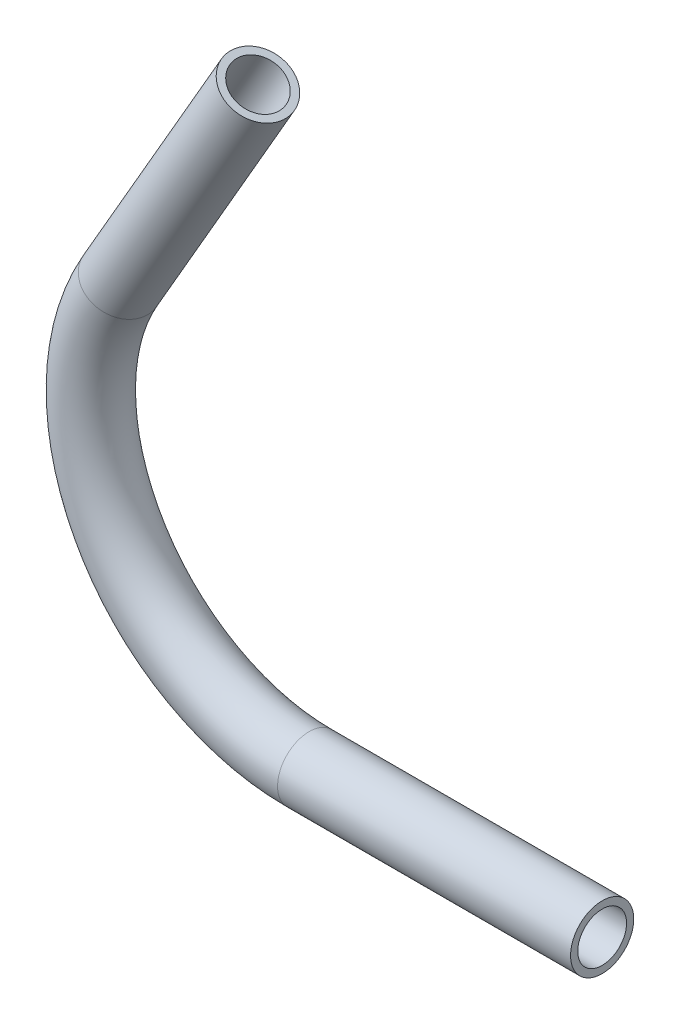
SolidWorks part; units mm, degrees
ref_plane "Plan1" through (0, 0, 0) normal (0, 0, 1) x (1, 0, 0)
ref_plane "Plan2" through (0, 0, 0) normal (0, 1, 0) x (1, 0, 0)
ref_plane "Plan3" through (0, 0, 0) normal (1, 0, 0) x (0, 0, -1)
sketch "Esquisse1" plane through (0, 0, 0) normal (0, 0, 1) x (1, 0, 0)
  line L0 (0, 0) -> (-90.448, 52.2202) construction
  line L1 (0, 0) -> (0, -92.4) construction
  arc A0 (-65.8179, 38) -> (0, -76) centre (0, 0) ccw
  dimension "D1" = 76
sketch "Esquisse2" plane through (0, 0, 0) normal (1, 0, 0) x (0, 0, -1)
  circle A0 centre (0, -76) radius 11
  circle A1 centre (0, -76) radius 8.5
  dimension "D1" = 22
  dimension "D3" = 17
  dimension "D2" = 76
sweep "Base-Balayage" add profiles "Esquisse2" path "Esquisse1"
sketch "Esquisse3" plane through (0, 0, 0) normal (1, 0, 0) x (0, 0, -1)
  circle A0 centre (0, -76) radius 8.5
  circle A1 centre (0, -76) radius 11
  dimension "D1" = 17
  dimension "D2" = 22
extrude "Boss.-Extru.1" add sketch "Esquisse3" along normal blind 102
sketch "Esquisse4" plane through (0, 0, 0) normal (0.5, 0.866, 0) x (-0.866, 0.5, 0)
  circle A0 centre (76, 0) radius 8.5
  circle A1 centre (76, 0) radius 11
  circle A2 centre (76, 0) radius 8.5 construction
  dimension "D1" = 17
  dimension "D2" = 22
extrude "Boss.-Extru.2" add sketch "Esquisse4" along normal blind 96
